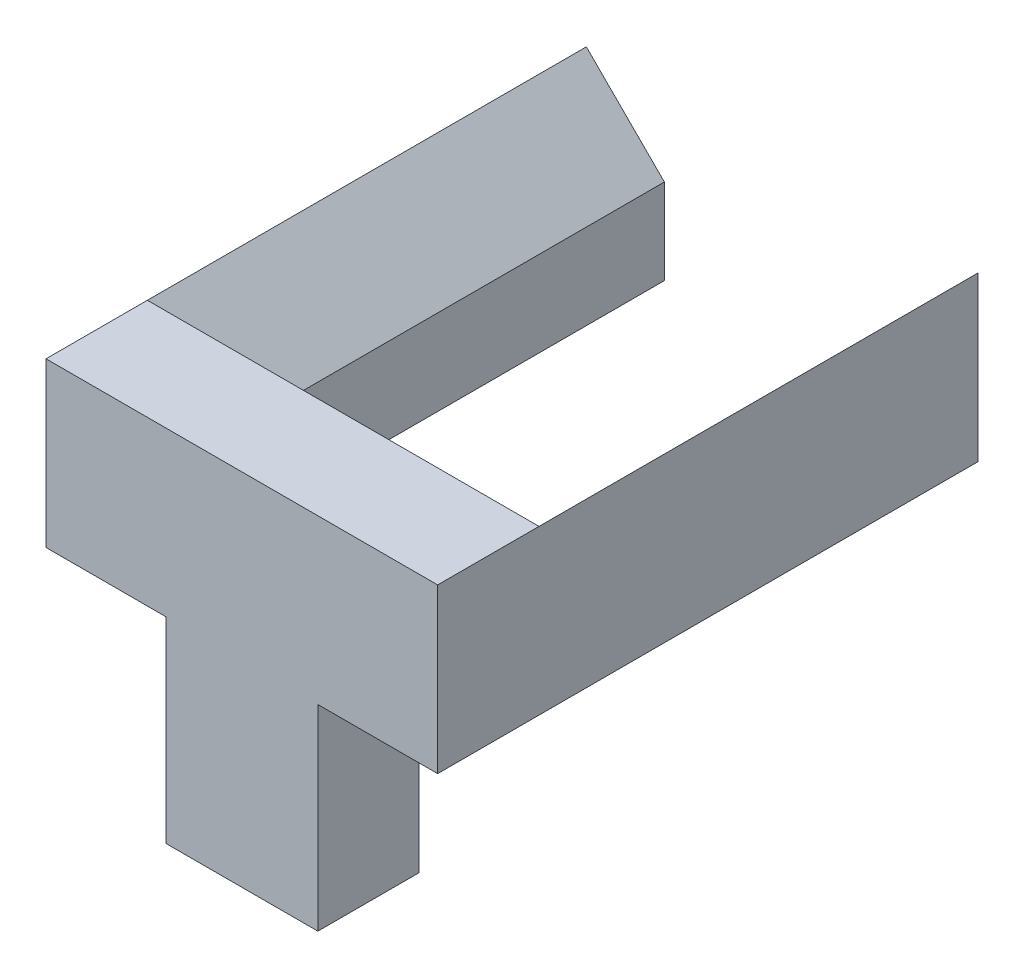
SolidWorks part; units mm, degrees
ref_plane "Front Plane" through (0, 0, 0) normal (0, 0, 1) x (1, 0, 0)
ref_plane "Top Plane" through (0, 0, 0) normal (0, 1, 0) x (1, 0, 0)
ref_plane "Right Plane" through (0, 0, 0) normal (1, 0, 0) x (0, 0, -1)
sketch "Sketch1" plane through (0, 0, 0) normal (0, 1, 0) x (1, 0, 0)
  line L0 (-13.9881, 12.8425) -> (-13.9881, -12.5575)
  line L1 (-13.9881, -12.5575) -> (24.1119, -12.5575)
  line L2 (24.1119, -12.5575) -> (24.1119, 12.8425)
  line L3 (24.1119, 12.8425) -> (-13.9881, 12.8425)
  line L4 (5.0619, 12.8425) -> (5.0619, -12.5575) construction
extrude "Boss-Extrude1" add sketch "Sketch1" along normal blind 90.1598 contours L3 L0 L1 L2
sketch "Sketch2" plane through (24.1119, 0, 0) normal (1, 0, 0) x (0, 0, -1)
  line L0 (-12.5575, 90.1598) -> (12.8425, 90.1598)
  line L1 (12.8425, 90.1598) -> (12.8425, 49.1998)
  line L2 (12.8425, 90.1598) -> (12.8425, 0) construction
  line L3 (12.8425, 49.1998) -> (-12.5575, 49.1998)
  line L4 (-12.5575, 90.1598) -> (-12.5575, 0) construction
  line L5 (-12.5575, 49.1998) -> (-12.5575, 90.1598)
extrude "Boss-Extrude2" add sketch "Sketch2" along normal blind 30.0228 contours L1 L3 L5 L0
sketch "Sketch3" plane through (-13.9881, 0, 0) normal (-1, 0, 0) x (0, 0, 1)
  line L0 (12.5575, 90.1598) -> (12.5575, 0) construction
  line L1 (-12.8425, 90.1598) -> (12.5575, 90.1598)
  line L2 (-12.8425, 90.1598) -> (-12.8425, 49.1998)
  line L3 (-12.8425, 49.1998) -> (12.5575, 49.1998)
  line L4 (12.5575, 90.1598) -> (12.5575, 49.1998)
extrude "Boss-Extrude3" add sketch "Sketch3" along normal blind 30.0228
sketch "Sketch4" plane through (0, 0, -12.8425) normal (0, 0, -1) x (-1, 0, 0)
  line L0 (-54.1347, 90.1598) -> (-54.1347, 49.1998)
  line L2 (-54.1347, 90.1598) -> (-34.5767, 70.6018)
  line L6 (-54.1347, 49.1998) -> (-24.1119, 49.1998) construction
  line L7 (-34.5767, 49.1998) -> (-54.1347, 49.1998)
  line L8 (-34.5767, 70.6018) -> (-34.5767, 49.1998)
extrude "Boss-Extrude4" add sketch "Sketch4" along normal blind 110.0074
sketch "Sketch5" plane through (0, 0, -12.8425) normal (0, 0, -1) x (-1, 0, 0)
  line L0 (44.0109, 90.1598) -> (44.0109, 49.1998)
  line L1 (44.0109, 49.1998) -> (24.4529, 49.1998)
  line L2 (44.0109, 49.1998) -> (13.9881, 49.1998) construction
  line L5 (44.0109, 90.1598) -> (24.4529, 70.6018)
  line L6 (24.4529, 70.6018) -> (24.4529, 49.1998)
extrude "Boss-Extrude5" add sketch "Sketch5" along normal blind 110.0074 contours L0 L1 L6 L5
sketch "Sketch8" plane through (0, 0, 0) normal (0, -1, 0) x (1, 0, 0)
  line L0 (5.0619, 12.5575) -> (5.0619, -12.8425) construction
  line L1 (-13.9881, 12.5575) -> (24.1119, 12.5575) construction
  line L2 (24.1119, -12.8425) -> (-13.9881, -12.8425) construction
  line L3 (5.0619, -0.1425) -> (15.0619, -0.1425) construction
  line L4 (5.0619, -0.1425) -> (-4.9381, -0.1425) construction
  circle A0 centre (-4.9381, -0.1425) radius 3.81
  circle A1 centre (15.0619, -0.1425) radius 3.81
  dimension "D1" = 7.62
  dimension "D2" = 7.62
extrude "Cut-Extrude1" cut sketch "Sketch8" against normal blind 25.4
